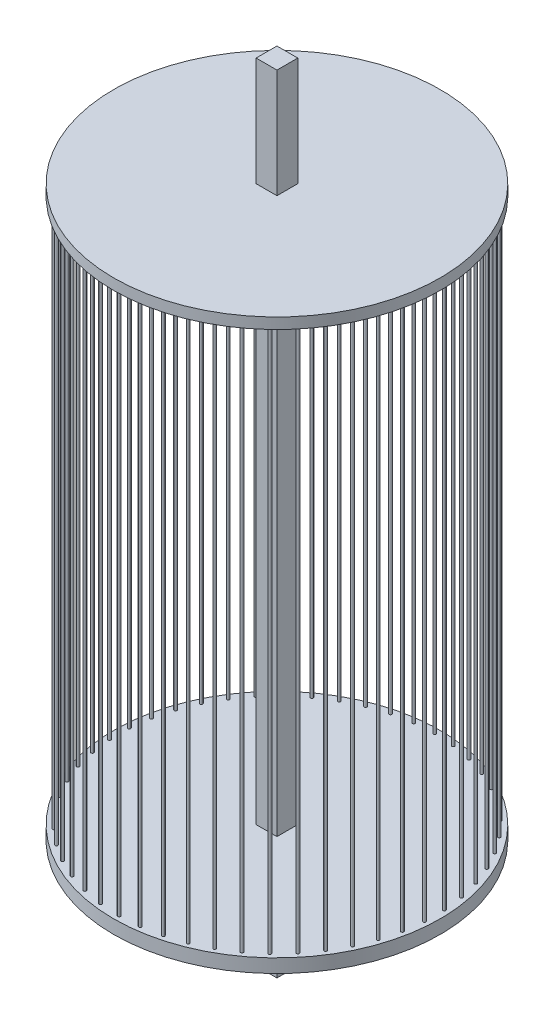
SolidWorks part; units mm, degrees
ref_plane "Front Plane" through (0, 0, 0) normal (0, 0, 1) x (1, 0, 0)
ref_plane "Top Plane" through (0, 0, 0) normal (0, 1, 0) x (1, 0, 0)
ref_plane "Right Plane" through (0, 0, 0) normal (1, 0, 0) x (0, 0, -1)
sketch "Sketch1" plane through (0, 0, 0) normal (0, 1, 0) x (1, 0, 0)
  circle A0 centre (0, 0) radius 76.2
  dimension "D1" = 152.4
  dimension "D2" = 0
extrude "Boss-Extrude1" add sketch "Sketch1" along normal blind 6.35
sketch "Sketch3" plane through (0, 6.35, 0) normal (0, 1, 0) x (1, 0, 0)
  line L1 (-4.8617, -4.8617) -> (4.8617, -4.8617)
  line L2 (-4.8617, -4.8617) -> (-4.8617, 4.8617)
  line L3 (-4.8617, 4.8617) -> (4.8617, 4.8617)
  line L4 (4.8617, -4.8617) -> (4.8617, 4.8617)
  line L5 (-4.8617, -4.8617) -> (4.8617, 4.8617) construction
  line L6 (-4.8617, 4.8617) -> (4.8617, -4.8617) construction
  point P0 (0, 0)
  dimension "D1" = 9.7234
  dimension "D2" = 9.7234
extrude "Boss-Extrude2" add sketch "Sketch3" along normal blind 254
sketch "Sketch4" plane through (0, 260.35, 0) normal (0, 1, 0) x (1, 0, 0)
  circle A0 centre (0, 0) radius 76.2
extrude "Boss-Extrude3" add sketch "Sketch4" along normal blind 5.08
sketch "Sketch5" plane through (0, 6.35, 0) normal (0, 1, 0) x (1, 0, 0)
  line L0 (0, 76.2) -> (0, 0) construction
  circle A1 centre (0, 0) radius 76.2 construction
  circle A2 centre (0, 73.66) radius 0.635
  circle A3 centre (9.232, 73.0792) radius 0.635
  circle A4 centre (18.3185, 71.3458) radius 0.635
  circle A5 centre (27.1161, 68.4873) radius 0.635
  circle A6 centre (35.486, 64.5488) radius 0.635
  circle A7 centre (43.2963, 59.5922) radius 0.635
  circle A8 centre (50.4237, 53.6958) radius 0.635
  circle A9 centre (56.756, 46.9527) radius 0.635
  circle A10 centre (62.1932, 39.469) radius 0.635
  circle A11 centre (66.6496, 31.3629) radius 0.635
  circle A12 centre (70.0548, 22.7622) radius 0.635
  circle A13 centre (72.3553, 13.8025) radius 0.635
  circle A14 centre (73.5146, 4.6251) radius 0.635
  circle A15 centre (73.5146, -4.6251) radius 0.635
  circle A16 centre (72.3553, -13.8025) radius 0.635
  circle A17 centre (70.0548, -22.7622) radius 0.635
  circle A18 centre (66.6496, -31.3629) radius 0.635
  circle A19 centre (62.1932, -39.469) radius 0.635
  circle A20 centre (56.756, -46.9527) radius 0.635
  circle A21 centre (50.4237, -53.6958) radius 0.635
  circle A22 centre (43.2963, -59.5922) radius 0.635
  circle A23 centre (35.486, -64.5488) radius 0.635
  circle A24 centre (27.1161, -68.4873) radius 0.635
  circle A25 centre (18.3185, -71.3458) radius 0.635
  circle A26 centre (9.232, -73.0792) radius 0.635
  circle A27 centre (0, -73.66) radius 0.635
  circle A28 centre (-9.232, -73.0792) radius 0.635
  circle A29 centre (-18.3185, -71.3458) radius 0.635
  circle A30 centre (-27.1161, -68.4873) radius 0.635
  circle A31 centre (-35.486, -64.5488) radius 0.635
  circle A32 centre (-43.2963, -59.5922) radius 0.635
  circle A33 centre (-50.4237, -53.6958) radius 0.635
  circle A34 centre (-56.756, -46.9527) radius 0.635
  circle A35 centre (-62.1932, -39.469) radius 0.635
  circle A36 centre (-66.6496, -31.3629) radius 0.635
  circle A37 centre (-70.0548, -22.7622) radius 0.635
  circle A38 centre (-72.3553, -13.8025) radius 0.635
  circle A39 centre (-73.5146, -4.6251) radius 0.635
  circle A40 centre (-73.5146, 4.6251) radius 0.635
  circle A41 centre (-72.3553, 13.8025) radius 0.635
  circle A42 centre (-70.0548, 22.7622) radius 0.635
  circle A43 centre (-66.6496, 31.3629) radius 0.635
  circle A44 centre (-62.1932, 39.469) radius 0.635
  circle A45 centre (-56.756, 46.9527) radius 0.635
  circle A46 centre (-50.4237, 53.6958) radius 0.635
  circle A47 centre (-43.2963, 59.5922) radius 0.635
  circle A48 centre (-35.486, 64.5488) radius 0.635
  circle A49 centre (-27.1161, 68.4873) radius 0.635
  circle A50 centre (-18.3185, 71.3458) radius 0.635
  circle A51 centre (-9.232, 73.0792) radius 0.635
  point P108 (0, 0)
  dimension "D2" = 1.27
  dimension "D1" = 2.54
  dimension "D3" = 50
extrude "Boss-Extrude4" add sketch "Sketch5" along normal blind 254
sketch "Sketch6" plane through (0, 265.43, 0) normal (0, 1, 0) x (1, 0, 0)
  line L1 (-4.8617, -4.8617) -> (4.8617, -4.8617)
  line L2 (-4.8617, -4.8617) -> (-4.8617, 4.8617)
  line L3 (-4.8617, 4.8617) -> (4.8617, 4.8617)
  line L4 (4.8617, -4.8617) -> (4.8617, 4.8617)
  line L5 (-4.8617, -4.8617) -> (4.8617, 4.8617) construction
  line L6 (-4.8617, 4.8617) -> (4.8617, -4.8617) construction
  point P0 (0, 0)
  dimension "D1" = 9.7234
  dimension "D2" = 9.7234
extrude "Boss-Extrude5" add sketch "Sketch6" along normal blind 50.8
sketch "Sketch7" plane through (0, 0, 0) normal (0, -1, 0) x (1, 0, 0)
  line L1 (-4.8617, 4.8617) -> (4.8617, 4.8617)
  line L2 (-4.8617, 4.8617) -> (-4.8617, -4.8617)
  line L3 (-4.8617, -4.8617) -> (4.8617, -4.8617)
  line L4 (4.8617, 4.8617) -> (4.8617, -4.8617)
  line L5 (-4.8617, 4.8617) -> (4.8617, -4.8617) construction
  line L6 (-4.8617, -4.8617) -> (4.8617, 4.8617) construction
  point P0 (0, 0)
  dimension "D1" = 9.7234
  dimension "D2" = 9.7234
extrude "Boss-Extrude6" add sketch "Sketch7" along normal blind 50.8
